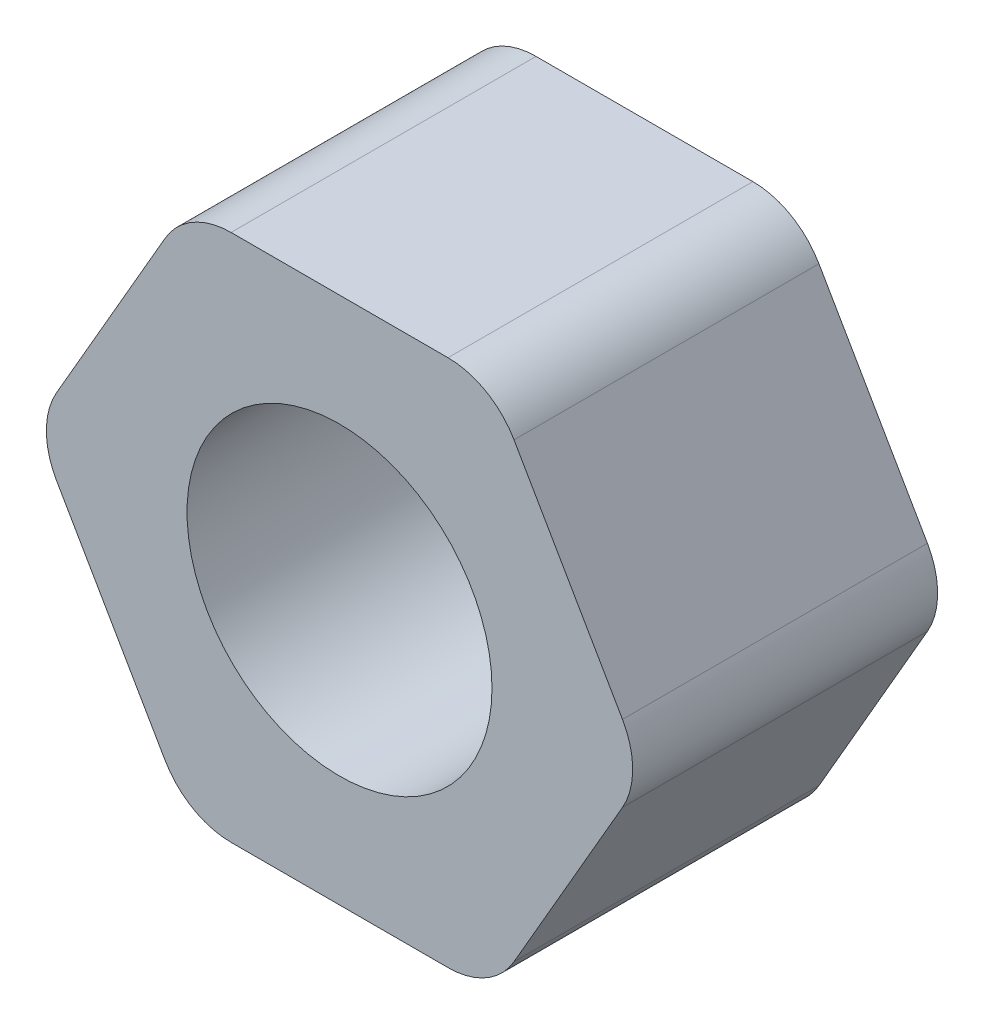
SolidWorks part; units mm, degrees
ref_plane "Front Plane" through (0, 0, 0) normal (0, 0, 1) x (1, 0, 0)
ref_plane "Top Plane" through (0, 0, 0) normal (0, 1, 0) x (1, 0, 0)
ref_plane "Right Plane" through (0, 0, 0) normal (1, 0, 0) x (0, 0, -1)
sketch "Sketch1" plane through (0, 0, 0) normal (0, 0, 1) x (1, 0, 0)
  line L1 (3.7113, 0.5) -> (2.2887, 2.9641)
  line L2 (1.4226, 3.4641) -> (-1.4226, 3.4641)
  line L3 (-2.2887, 2.9641) -> (-3.7113, 0.5)
  line L4 (-3.7113, -0.5) -> (-2.2887, -2.9641)
  line L5 (-1.4226, -3.4641) -> (1.4226, -3.4641)
  line L6 (2.2887, -2.9641) -> (3.7113, -0.5)
  circle A0 centre (0, 0) radius 3.4641 construction
  circle A1 centre (0, 0) radius 2
  arc A2 (-3.7113, 0.5) -> (-3.7113, -0.5) centre (-2.8453, 0) ccw
  arc A3 (-1.4226, 3.4641) -> (-2.2887, 2.9641) centre (-1.4226, 2.4641) ccw
  arc A4 (2.2887, 2.9641) -> (1.4226, 3.4641) centre (1.4226, 2.4641) ccw
  arc A5 (3.7113, 0.5) -> (3.7113, -0.5) centre (2.8453, 0) cw
  arc A6 (1.4226, -3.4641) -> (2.2887, -2.9641) centre (1.4226, -2.4641) ccw
  arc A7 (-2.2887, -2.9641) -> (-1.4226, -3.4641) centre (-1.4226, -2.4641) ccw
  point P10 (0, -3.4641)
  dimension "D1" = 4
  dimension "D2" = 3.4641
  dimension "D3" = 1
extrude "Boss-Extrude1" add sketch "Sketch1" along normal blind 4
